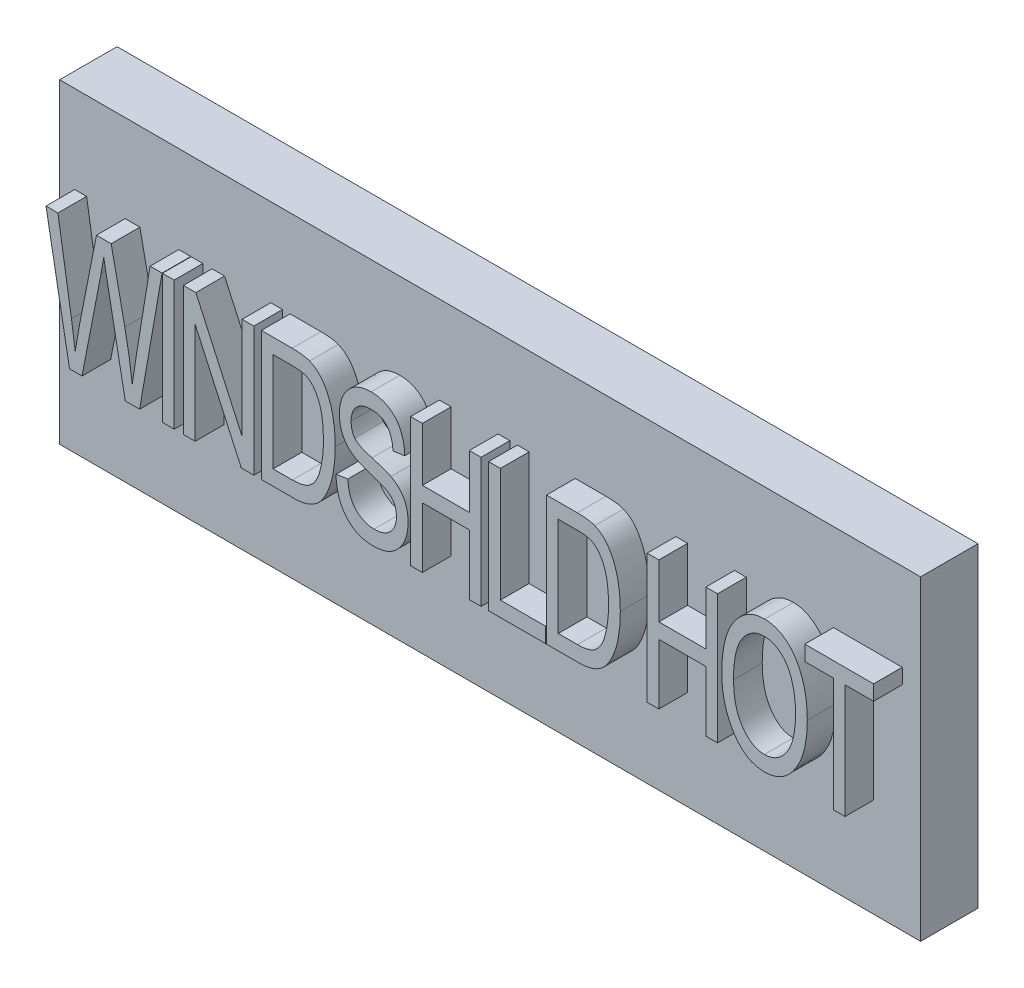
SolidWorks part; units mm, degrees
ref_plane "Front Plane" through (0, 0, 0) normal (0, 0, 1) x (1, 0, 0)
ref_plane "Top Plane" through (0, 0, 0) normal (0, 1, 0) x (1, 0, 0)
ref_plane "Right Plane" through (0, 0, 0) normal (1, 0, 0) x (0, 0, -1)
sketch "Sketch1" plane through (0, 0, 0) normal (0, 0, 1) x (1, 0, 0)
  line L1 (-51.24, 31.58) -> (-21.24, 31.58)
  line L2 (-51.24, 31.58) -> (-51.24, 20.58)
  line L3 (-51.24, 20.58) -> (-21.24, 20.58)
  line L4 (-21.24, 31.58) -> (-21.24, 20.58)
  dimension "D1" = 30
  dimension "D2" = 11
extrude "Boss-Extrude1" add sketch "Sketch1" along normal blind 2
sketch "Sketch2" plane through (0, 0, 2) normal (0, 0, 1) x (1, 0, 0)
  text T0 "WINDSHLD HOT" font "Arial Narrow" height 4.5
extrude "Boss-Extrude2" add sketch "Sketch2" along normal blind 1
